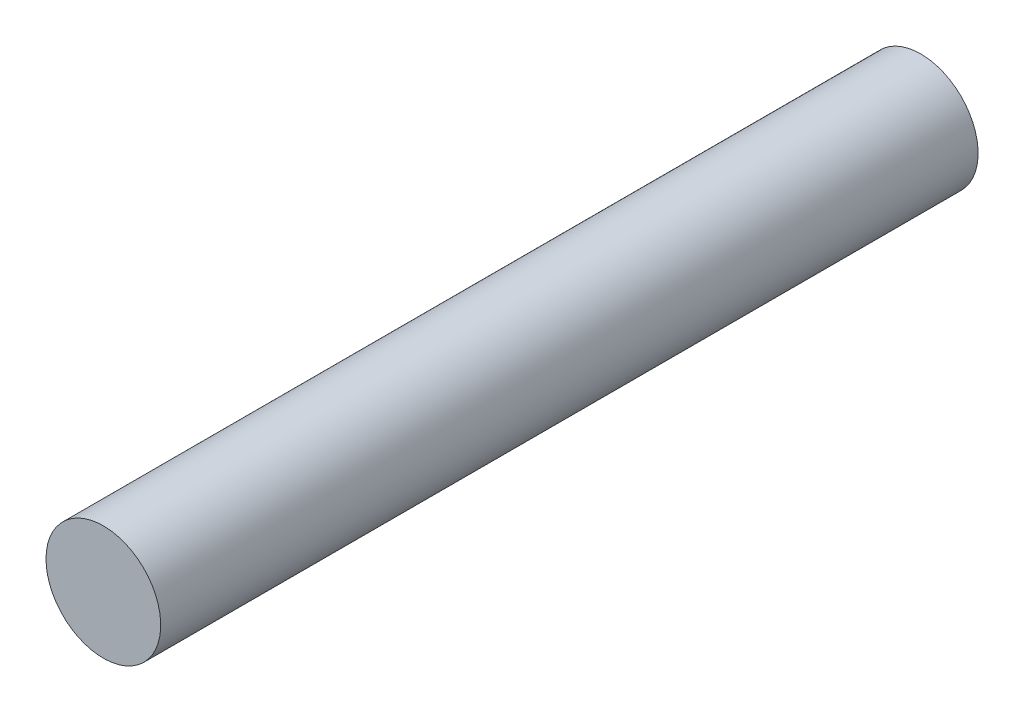
SolidWorks part; units mm, degrees
ref_plane "Front Plane" through (0, 0, 0) normal (0, 0, 1) x (1, 0, 0)
ref_plane "Top Plane" through (0, 0, 0) normal (0, 1, 0) x (1, 0, 0)
ref_plane "Right Plane" through (0, 0, 0) normal (1, 0, 0) x (0, 0, -1)
sketch "Sketch1" plane through (0, 0, 0) normal (0, 0, 1) x (1, 0, 0)
  circle A0 centre (0, 0) radius 4
  dimension "D1" = 8
extrude "Boss-Extrude1" add sketch "Sketch1" along normal blind 57
